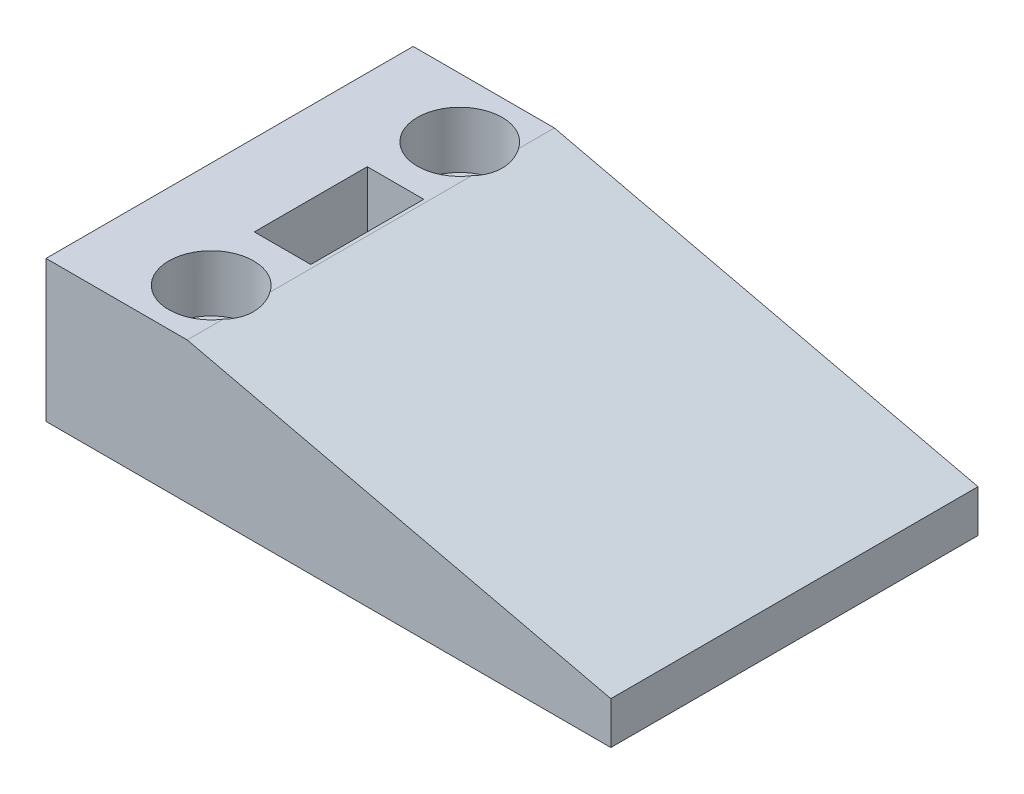
SolidWorks part; units mm, degrees
ref_plane "Front Plane" through (0, 0, 0) normal (0, 0, 1) x (1, 0, 0)
ref_plane "Top Plane" through (0, 0, 0) normal (0, 1, 0) x (1, 0, 0)
ref_plane "Right Plane" through (0, 0, 0) normal (1, 0, 0) x (0, 0, -1)
sketch "Sketch1" plane through (0, 0, 0) normal (0, 0, 1) x (1, 0, 0)
  line L0 (10, 10) -> (40, 3)
  line L1 (0, 0) -> (40, 0)
  line L2 (0, 0) -> (0, 3)
  line L3 (0, 3) -> (40, 3)
  line L4 (40, 0) -> (40, 3)
  line L5 (0, 3) -> (10, 3)
  line L6 (0, 3) -> (0, 10)
  line L7 (0, 10) -> (10, 10)
  line L8 (10, 3) -> (10, 10)
  dimension "D1" = 3
  dimension "D2" = 40
  dimension "D3" = 10
  dimension "D4" = 7
extrude "Boss-Extrude1" add sketch "Sketch1" along normal blind 26 contours L1 L4 L3 L2 | L8 L3 L0 | L3 L8 L7 L6
sketch "Sketch3" plane through (0, 0, 0) normal (0, -1, 0) x (1, 0, 0)
  line L0 (0, 26) -> (0, 0) construction
  line L1 (0, 26) -> (40, 26) construction
  line L3 (5.75, 17) -> (9.75, 17)
  line L4 (5.75, 17) -> (5.75, 9)
  line L5 (5.75, 9) -> (9.75, 9)
  line L6 (9.75, 17) -> (9.75, 9)
  circle A0 centre (7.5, 21.8) radius 1.725
  circle A1 centre (7.5, 4.2) radius 1.725
  dimension "D1" = 3.45
  dimension "D2" = 7.5
  dimension "D3" = 4.2
  dimension "D5" = 8
  dimension "D6" = 9
  dimension "D7" = 4
  dimension "D8" = 5.75
  dimension "D4" = 2
extrude "Cut-Extrude1" cut sketch "Sketch3" against normal through all
sketch "Sketch4" plane through (0, 10, 0) normal (0, 1, 0) x (1, 0, 0)
  circle A0 centre (7.5, -4.2) radius 3
  circle A2 centre (7.5, -4.2) radius 1.725 construction
  circle A3 centre (7.5, -21.8) radius 3
  circle A4 centre (7.5, -21.8) radius 1.725 construction
  dimension "D1" = 6
  dimension "D2" = 6
extrude "Cut-Extrude2" cut sketch "Sketch4" against normal blind 4
